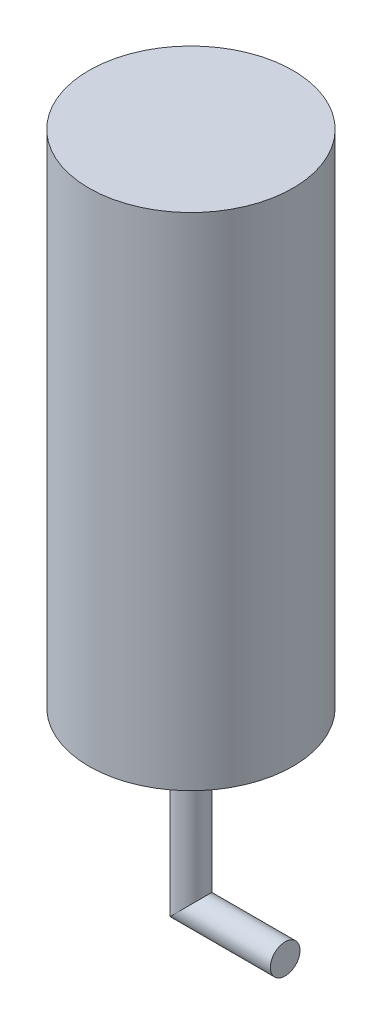
SolidWorks part; units mm, degrees
ref_plane "Front Plane" through (0, 0, 0) normal (0, 0, 1) x (1, 0, 0)
ref_plane "Top Plane" through (0, 0, 0) normal (0, 1, 0) x (1, 0, 0)
ref_plane "Right Plane" through (0, 0, 0) normal (1, 0, 0) x (0, 0, -1)
sketch "Sketch1" plane through (0, 0, 0) normal (0, 1, 0) x (1, 0, 0)
  circle A0 centre (0, 0) radius 2.75
  dimension "D1" = 5.5
extrude "Boss-Extrude1" add sketch "Sketch1" along normal blind 13.5
sketch3d "3DSketch1"
  line L0 (0, 0, 0) -> (0, -4.6, 0)
  line L2 (0, -4.6, 0) -> (2.54, -4.6, 0)
  dimension "D3" = 2.54
  dimension "D1" = 90
  dimension "D2" = 4.6
sketch "Sketch4" plane through (0, 0, 0) normal (0, -1, 0) x (1, 0, 0)
  circle A0 centre (0, 0) radius 0.4
  dimension "D1" = 0.8
sweep "Sweep1" add profiles "Sketch4" path "3DSketch1"
